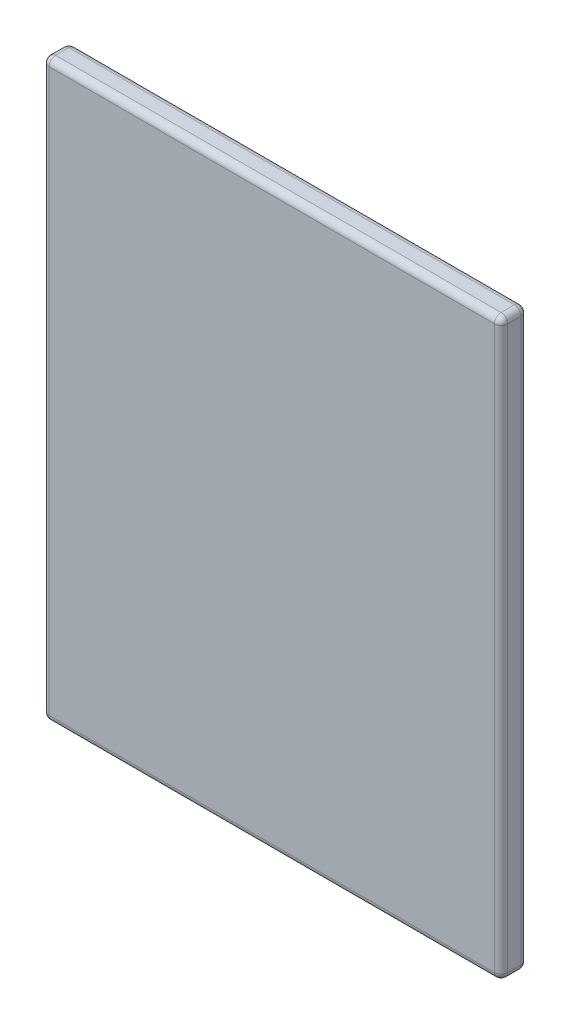
SolidWorks part; units mm, degrees
ref_plane "Front Plane" through (0, 0, 0) normal (0, 0, 1) x (1, 0, 0)
ref_plane "Top Plane" through (0, 0, 0) normal (0, 1, 0) x (1, 0, 0)
ref_plane "Right Plane" through (0, 0, 0) normal (1, 0, 0) x (0, 0, -1)
sketch "Sketch1" plane through (0, 0, 0) normal (0, 0, 1) x (1, 0, 0)
  line L1 (-17.35, -21.75) -> (17.35, -21.75)
  line L2 (-17.35, -21.75) -> (-17.35, 21.75)
  line L3 (-17.35, 21.75) -> (17.35, 21.75)
  line L4 (17.35, -21.75) -> (17.35, 21.75)
  line L5 (-17.35, -21.75) -> (17.35, 21.75) construction
  line L6 (-17.35, 21.75) -> (17.35, -21.75) construction
  point P0 (0, 0)
  dimension "D1" = 34.7
  dimension "D2" = 43.5
extrude "Boss-Extrude1" add sketch "Sketch1" along normal blind 2
fillet "Fillet1" radius 0.5 12 edges at (0, -21.75, 2) (0, -21.75, 0) (-17.35, 0, 2) (-17.35, -21.75, 1) (-17.35, 0, 0) (0, 21.75, 2) (-17.35, 21.75, 1) (0, 21.75, 0) (17.35, -21.75, 1) (17.35, 0, 2) (17.35, 21.75, 1) (17.35, 0, 0)
